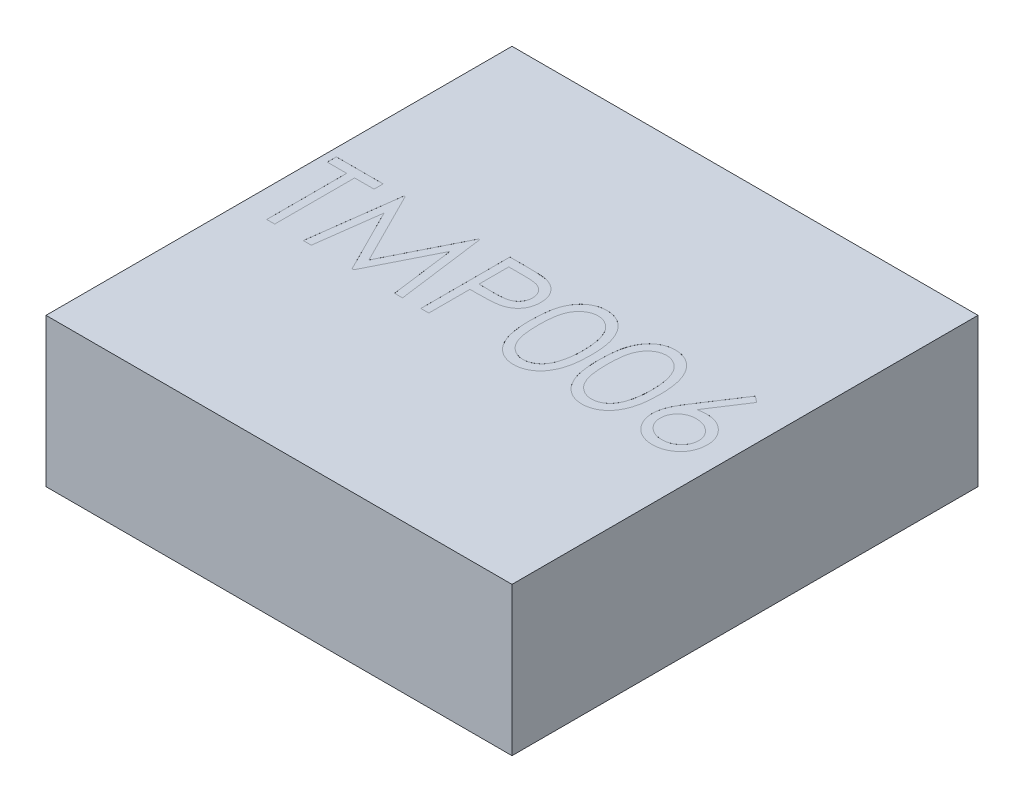
SolidWorks part; units mm, degrees
ref_plane "Piano frontale" through (0, 0, 0) normal (0, 0, 1) x (1, 0, 0)
ref_plane "Piano superiore" through (0, 0, 0) normal (0, 1, 0) x (1, 0, 0)
ref_plane "Piano destro" through (0, 0, 0) normal (1, 0, 0) x (0, 0, -1)
sketch "Schizzo1" plane through (0, 0, 0) normal (0, 1, 0) x (1, 0, 0)
  line L1 (-22.1319, 40.5272) -> (-20.5619, 40.5272)
  line L2 (-22.1319, 40.5272) -> (-22.1319, 38.9572)
  line L3 (-22.1319, 38.9572) -> (-20.5619, 38.9572)
  line L4 (-20.5619, 40.5272) -> (-20.5619, 38.9572)
  dimension "D1" = 1.57
  dimension "D2" = 1.57
extrude "Estrusione-Estrusione1" add sketch "Schizzo1" along normal blind 0.5
sketch "Schizzo2" plane through (0, 0.5, 0) normal (0, 1, 0) x (1, 0, 0)
  text T0 "TMP006\r\n" font "Century Gothic" height 0.3
extrude "Taglio-Estrusione1" cut sketch "Schizzo2" against normal blind 0.0001
